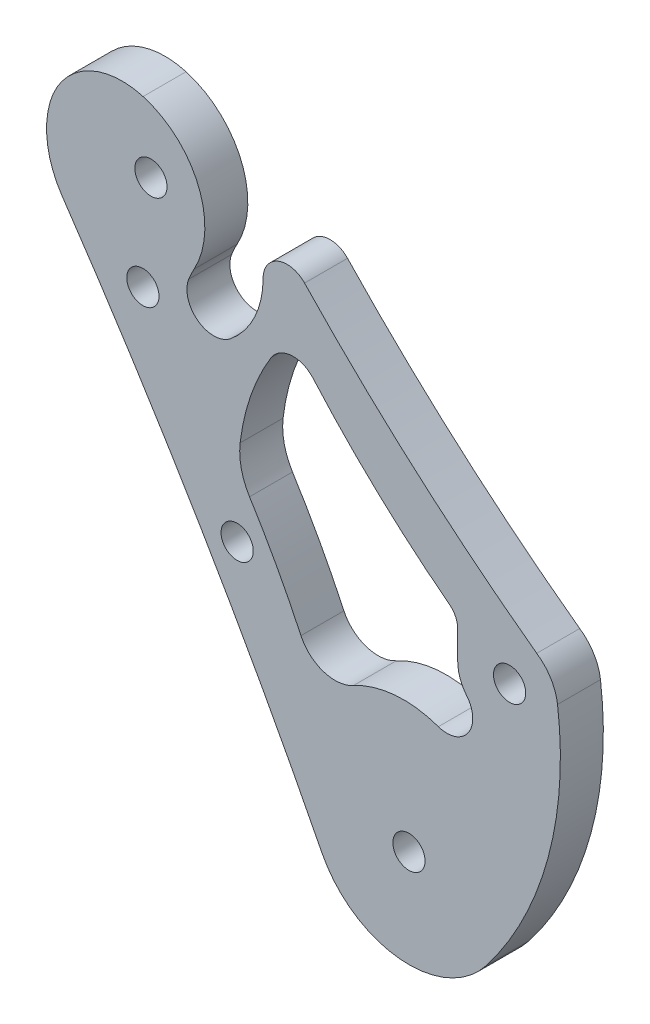
SolidWorks part; units mm, degrees
ref_plane "Plan de face" through (0, 0, 0) normal (0, 0, 1) x (1, 0, 0)
ref_plane "Plan de dessus" through (0, 0, 0) normal (0, 1, 0) x (1, 0, 0)
ref_plane "Plan de droite" through (0, 0, 0) normal (1, 0, 0) x (0, 0, -1)
sketch "Esquisse1" plane through (0, 0, 0) normal (0, 0, 1) x (1, 0, 0)
  line L0 (73.4009, 459.4032) -> (81.5095, 453.5509) construction
  line L1 (96.8497, 30.849) -> (96.8497, 33.4747)
  circle A1 centre (68.2855, 55.5604) radius 1.5
  circle A2 centre (101.6821, 31.4335) radius 1.5
  circle A3 centre (92.3124, 13.2001) radius 1.5
  circle A4 centre (67.5355, 46.3604) radius 1.5011
  arc A6 (60.0269, 49.9216) -> (84.1953, 9.0864) centre (-239.9507, -155.19) cw
  arc A7 (84.1953, 9.0864) -> (99.5091, 7.6308) centre (92.3124, 13.2001) ccw
  arc A8 (99.5091, 7.6308) -> (106.1459, 32.003) centre (73.4112, 27.8273) ccw
  arc A9 (106.1459, 32.003) -> (104.2103, 35.1562) centre (101.6821, 31.4335) ccw
  arc A11 (77.4672, 34.4096) -> (82.254, 25.6053) centre (6.216, -10.033) cw
  arc A12 (82.254, 25.6053) -> (87.1342, 24.0178) centre (85.4377, 27.0974) ccw
  arc A13 (87.1342, 24.0178) -> (95.0512, 24.6624) centre (91.8101, 15.5295) cw
  arc A14 (95.0512, 24.6624) -> (97.7092, 28.4438) centre (95.8535, 26.9233) ccw
  arc A15 (97.7092, 28.4438) -> (96.8497, 30.849) centre (100.6448, 30.849) cw
  arc A16 (96.8497, 33.4747) -> (96.0818, 35.0326) centre (94.8854, 33.4747) ccw
  arc A17 (96.0818, 35.0326) -> (83.3729, 46.9299) centre (150.5127, 105.913) cw
  arc A18 (83.3729, 46.9299) -> (79.4458, 46.5889) centre (81.5348, 45.315) ccw
  arc A19 (79.4458, 46.5889) -> (76.5917, 38.3167) centre (96.9244, 35.93) ccw
  arc A20 (76.5917, 38.3167) -> (77.4672, 34.4096) centre (82.6003, 37.6114) ccw
  arc A21 (74.9462, 53.0521) -> (69.969, 62.4758) centre (68.2855, 55.5604) ccw construction
  arc A22 (77.4672, 52.4638) -> (70.5815, 64.9743) centre (68.2855, 55.5604) ccw construction
  arc A23 (60.0269, 49.9216) -> (58.8919, 56.9478) centre (66.9298, 54.6414) cw
  arc A24 (58.8919, 56.9478) -> (67.5541, 61.7268) centre (65.6039, 55.0218) cw
  arc A25 (67.5541, 61.7268) -> (72.3057, 50.1913) centre (65.3248, 54.0622) cw
  arc A26 (72.3057, 50.1913) -> (71.8053, 49.1246) centre (79.926, 45.9659) ccw
  arc A27 (71.8053, 49.1246) -> (75.7249, 46.2888) centre (74.1352, 48.2183) ccw
  arc A28 (75.7249, 46.2888) -> (78.73, 52.6621) centre (70.4773, 52.6582) ccw
  arc A29 (78.73, 52.6621) -> (82.5901, 54.2021) centre (80.9668, 52.6631) cw
  arc A30 (82.5901, 54.2021) -> (104.2103, 35.1562) centre (199.0673, 164.6287) ccw
  point P57 (75.1828, 48.1594)
  point P58 (79.4458, 53.3982)
  point P59 (72.2339, 47.2505)
  point P60 (74.1352, 48.2183)
  point P61 (78.73, 52.6631)
  dimension "D2" = 3
  dimension "D8" = 2.5
  dimension "D9" = 363.3969
  dimension "D10" = 9.1
  dimension "D11" = 33
  dimension "D12" = 4.5
  dimension "D1" = 10
  dimension "D3" = 41.2
  dimension "D4" = 48.7
  dimension "D5" = 20.5
  dimension "D6" = 9.2
  dimension "D7" = 0.75
extrude "Boss.-Extru.1" add sketch "Esquisse1" along normal blind 4
sketch "Esquisse2" plane through (0, 0, 4) normal (0, 0, 1) x (1, 0, 0)
  circle A0 centre (76.3124, 30.2001) radius 1.5
  circle A1 centre (92.3124, 13.2001) radius 1.5 construction
  dimension "D1" = 17
  dimension "D3" = 3
  dimension "D2" = 16
extrude "Enlèv. mat.-Extru.1" cut sketch "Esquisse2" against normal up to next
